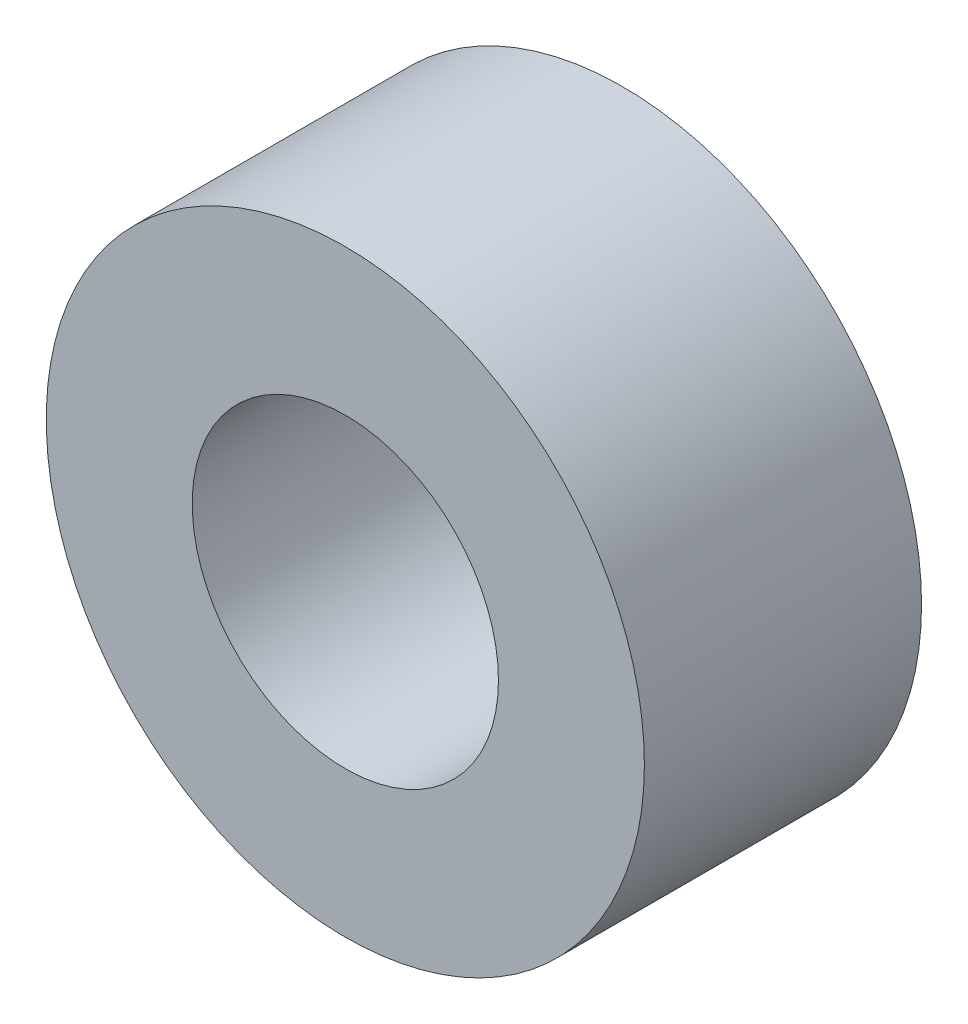
SolidWorks part; units mm, degrees
material "6061-T6 (SS)"
ref_plane "Front Plane" through (0, 0, 0) normal (0, 0, 1) x (1, 0, 0)
ref_plane "Top Plane" through (0, 0, 0) normal (0, 1, 0) x (1, 0, 0)
ref_plane "Right Plane" through (0, 0, 0) normal (1, 0, 0) x (0, 0, -1)
sketch "Sketch1" plane through (0, 0, 0) normal (1, 0, 0) x (0, 0, -1)
  line L0 (0, 0) -> (0, 3.2512) construction
  line L1 (0, 0) -> (6.8636, 0) construction
  line L2 (0, 3.2512) -> (0, 6.35)
  line L3 (0, 6.35) -> (5.8849, 6.35)
  line L4 (5.8849, 6.35) -> (5.8849, 4.6736)
  line L5 (5.8849, 4.6736) -> (6.3929, 4.6736)
  line L6 (6.3929, 4.6736) -> (6.3929, 3.2512)
  line L7 (6.3929, 3.2512) -> (0, 3.2512)
  point P6 (6.3929, 3.9624)
  dimension "D1" = 6.5024
  dimension "D2" = 6.35
  dimension "D3" = 4.6736
  dimension "D4" = 6.3929
  dimension "D5" = 0.508
revolve "Revolve1" add sketch "Sketch1" angle 360 about L1
